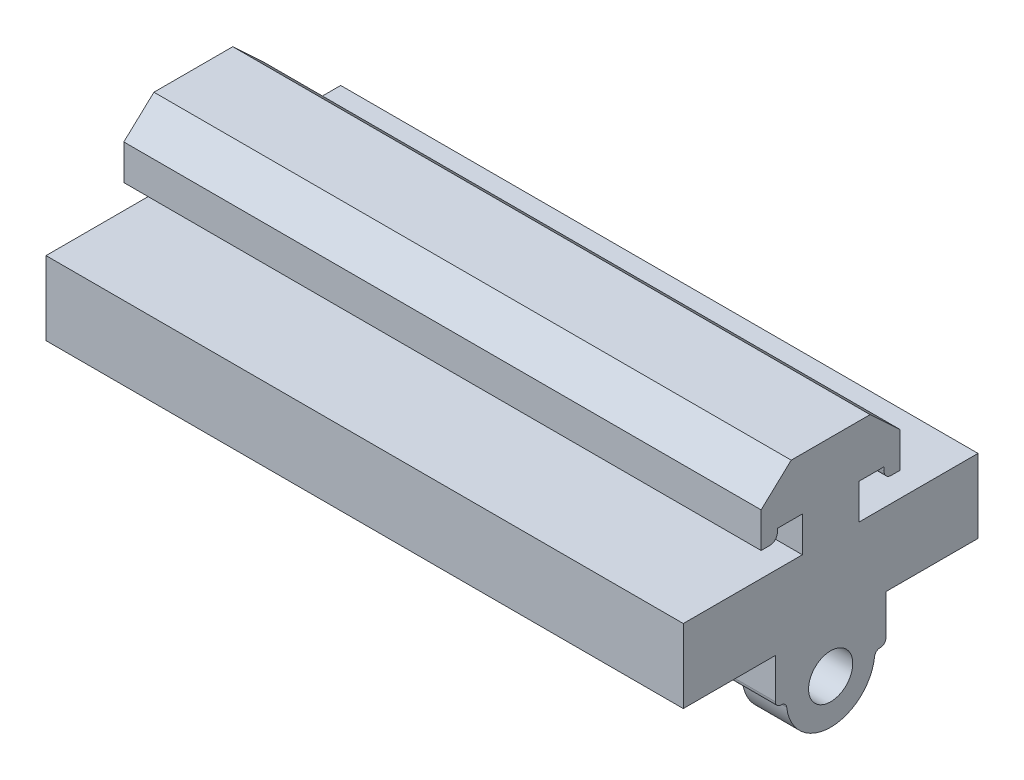
SolidWorks part; units mm, degrees
ref_plane "Front Plane" through (0, 0, 0) normal (0, 0, 1) x (1, 0, 0)
ref_plane "Top Plane" through (0, 0, 0) normal (0, 1, 0) x (1, 0, 0)
ref_plane "Right Plane" through (0, 0, 0) normal (1, 0, 0) x (0, 0, -1)
sketch "Sketch1" plane through (0, 0, 0) normal (0, 1, 0) x (1, 0, 0)
  line L1 (-37.25, -20) -> (37.25, -20)
  line L2 (-37.25, -20) -> (-37.25, 20)
  line L3 (-37.25, 20) -> (37.25, 20)
  line L4 (37.25, -20) -> (37.25, 20)
  line L5 (-37.25, -20) -> (37.25, 20) construction
  line L6 (-37.25, 20) -> (37.25, -20) construction
  point P0 (0, 0)
  dimension "D1" = 40
  dimension "D2" = 74.5
extrude "Boss-Extrude1" add sketch "Sketch1" along normal blind 10
sketch "Sketch2" plane through (37.25, 0, 0) normal (1, 0, 0) x (0, 0, -1)
  line L0 (-7.5, 0) -> (-7.5, -5.45)
  line L1 (-20, 0) -> (20, 0) construction
  line L2 (-6.75, -6.2) -> (-6.7082, -6.2)
  line L3 (7.5, -5.45) -> (7.5, 0)
  line L5 (0, 0) -> (0, 1.9909) construction
  line L6 (6.7082, -6.2) -> (6.75, -6.2)
  line L7 (-3, -6.2) -> (3, -6.2)
  line L8 (-20, 0) -> (-7.5, 0)
  line L9 (7.5, 0) -> (20, 0)
  line L12 (-20, 0) -> (20, 0)
  line L13 (20, 0) -> (20, 10)
  line L14 (20, 10) -> (-20, 10)
  line L15 (-20, 10) -> (-20, 0)
  line L17 (20, 0) -> (20, 10)
  line L18 (20, 10) -> (-20, 10)
  line L19 (-20, 10) -> (-20, 0)
  circle A0 centre (0, -6.2) radius 3
  arc A1 (-5.9628, -6.8667) -> (5.9628, -6.8667) centre (0, -6.2) ccw
  arc A2 (-5.9628, -6.8667) -> (-6.7082, -6.2) centre (-6.7082, -6.95) ccw
  arc A3 (-7.5, -5.45) -> (-6.75, -6.2) centre (-6.75, -5.45) ccw
  arc A4 (6.75, -6.2) -> (7.5, -5.45) centre (6.75, -5.45) ccw
  arc A5 (5.9628, -6.8667) -> (6.7082, -6.2) centre (6.7082, -6.95) cw
  point P25 (7.5, -6.2)
  point P28 (6, -6.2)
  dimension "D1" = 6
  dimension "D2" = 12
  dimension "D4" = 7.5
  dimension "D6" = 0.75
  dimension "D7" = 0.75
  dimension "D3" = 6.2
  dimension "D5" = 0
extrude "Boss-Extrude2" add sketch "Sketch2" along normal blind 6
mirror "Mirror1" about plane through (0, 0, 0) normal (1, 0, 0) of "Boss-Extrude2"
sketch "Sketch3" plane through (-43.25, 0, 0) normal (-1, 0, 0) x (0, 0, 1)
  line L0 (-4.1618, 10) -> (3.8382, 10)
  line L1 (-20, 10) -> (20, 10) construction
  line L2 (3.8382, 10) -> (3.8382, 14.8)
  line L3 (3.8382, 14.8) -> (7.2382, 14.8)
  line L4 (7.2382, 14.8) -> (7.2382, 14.3)
  line L5 (8.2382, 13.3) -> (9.4382, 13.3)
  line L6 (9.4382, 18.08) -> (9.4382, 14.8)
  line L7 (9.4382, 18.08) -> (5.3521, 21.88)
  line L8 (0, 10) -> (0, 13.289) construction
  line L9 (0, 0) -> (0, 3.0083) construction
  line L10 (9.4382, 14.8) -> (9.4382, 13.3)
  line L11 (-9.4382, 18.08) -> (-5.3521, 21.88)
  line L12 (-9.4382, 18.08) -> (-9.4382, 14.8)
  line L13 (-9.4382, 14.8) -> (-9.4382, 13.3)
  line L14 (-7.2382, 14.8) -> (-7.2382, 14.3)
  line L15 (-8.2382, 13.3) -> (-9.4382, 13.3)
  line L16 (-3.8382, 14.8) -> (-7.2382, 14.8)
  line L17 (-3.8382, 10) -> (-3.8382, 14.8)
  line L18 (-5.3521, 21.88) -> (5.3521, 21.88)
  arc A0 (7.2382, 14.3) -> (8.2382, 13.3) centre (8.2382, 14.3) ccw
  arc A1 (-7.2382, 14.3) -> (-8.2382, 13.3) centre (-8.2382, 14.3) cw
  line M10 (20, 10) -> (-20, 10)
  dimension "D9" = 1
  dimension "D1" = 8
  dimension "D2" = 4.8
  dimension "D3" = 1.5
  dimension "D4" = 3.28
  dimension "D5" = 3.8
  dimension "D6" = 5.58
  dimension "D7" = 2.2
  dimension "D8" = 5.6
extrude "Boss-Extrude3" add sketch "Sketch3" against normal up to surface (86.5 mm away) contours A1 L14 L16 L17 L2 L3 L4 A0 L5 L10 L6 L7 L18 L11 L12 L13 L15 M10 up to face at (43.25, -6.2, -3)
